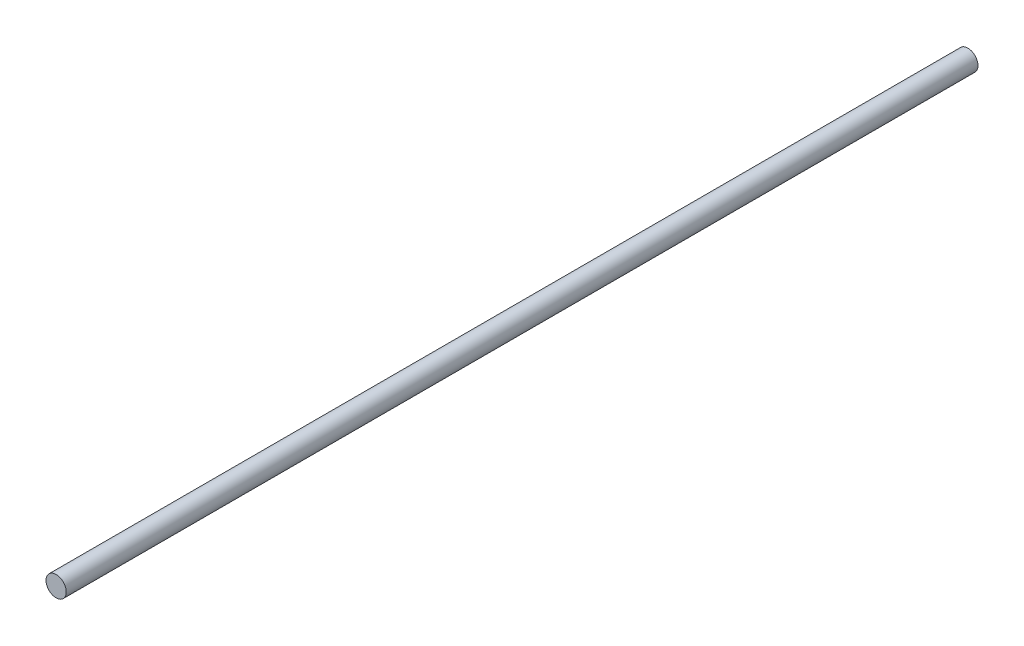
SolidWorks part; units mm, degrees
ref_plane "Front Plane" through (0, 0, 0) normal (0, 0, 1) x (1, 0, 0)
ref_plane "Top Plane" through (0, 0, 0) normal (0, 1, 0) x (1, 0, 0)
ref_plane "Right Plane" through (0, 0, 0) normal (1, 0, 0) x (0, 0, -1)
sketch "Sketch1" plane through (0, 0, 0) normal (0, 0, 1) x (1, 0, 0)
  circle A0 centre (0, 0) radius 3
extrude "Boss-Extrude1" add sketch "Sketch1" along normal blind 270
cosmetic thread "Cosmetic Thread1" parameters "D2"=4.891
